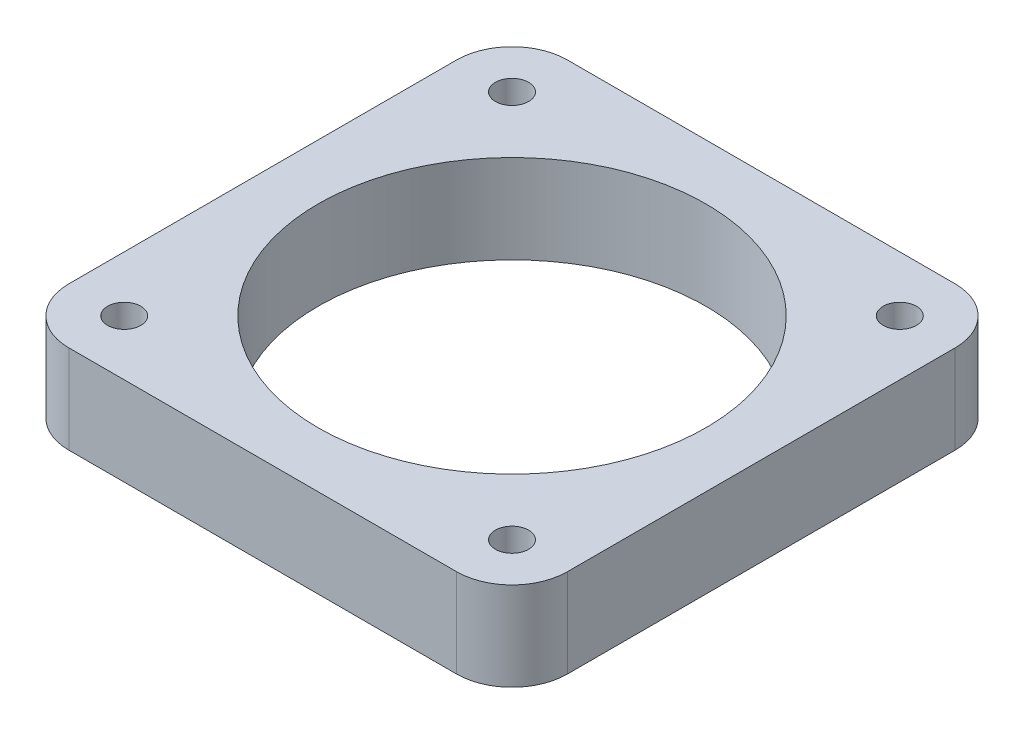
SolidWorks part; units mm, degrees
ref_plane "Front Plane" through (0, 0, 0) normal (0, 0, 1) x (1, 0, 0)
ref_plane "Top Plane" through (0, 0, 0) normal (0, 1, 0) x (1, 0, 0)
ref_plane "Right Plane" through (0, 0, 0) normal (1, 0, 0) x (0, 0, -1)
sketch "Sketch1" plane through (0, 0, 0) normal (0, 1, 0) x (1, 0, 0)
  line L1 (-22.5, -22.5) -> (22.5, -22.5)
  line L2 (-22.5, -22.5) -> (-22.5, 22.5)
  line L3 (-22.5, 22.5) -> (22.5, 22.5)
  line L4 (22.5, -22.5) -> (22.5, 22.5)
  line L5 (-22.5, -22.5) -> (22.5, 22.5) construction
  line L6 (-22.5, 22.5) -> (22.5, -22.5) construction
  line L7 (-17.5, -17.5) -> (17.5, -17.5)
  line L8 (-17.5, -17.5) -> (-17.5, 17.5)
  line L9 (-17.5, 17.5) -> (17.5, 17.5)
  line L10 (17.5, -17.5) -> (17.5, 17.5)
  line L11 (-17.5, -17.5) -> (17.5, 17.5) construction
  line L12 (-17.5, 17.5) -> (17.5, -17.5) construction
  circle A0 centre (0, 0) radius 17.5
  circle A1 centre (-17.5, 17.5) radius 1.5
  circle A2 centre (17.5, 17.5) radius 1.5
  circle A3 centre (17.5, -17.5) radius 1.5
  circle A4 centre (-17.5, -17.5) radius 1.5
  point P0 (0, 0)
  point P5 (0, 0)
  dimension "D1" = 5
  dimension "D2" = 35
  dimension "D3" = 35
extrude "Boss-Extrude1" add sketch "Sketch1" along normal blind 8 contours A4 L7 A3 L10 A2 L9 A1 L8 A0 | L1 L4 L3 L2 A4 L8 A1 L9 A2 L10 A3 L7 | A4 L7 A0 L8 | A1 L8 A0 L9 | A2 L9 A0 L10
fillet "Fillet1" radius 5 4 edges at (-22.5, 4, 22.5) (-22.5, 4, -22.5) (22.5, 4, -22.5) (22.5, 4, 22.5)
